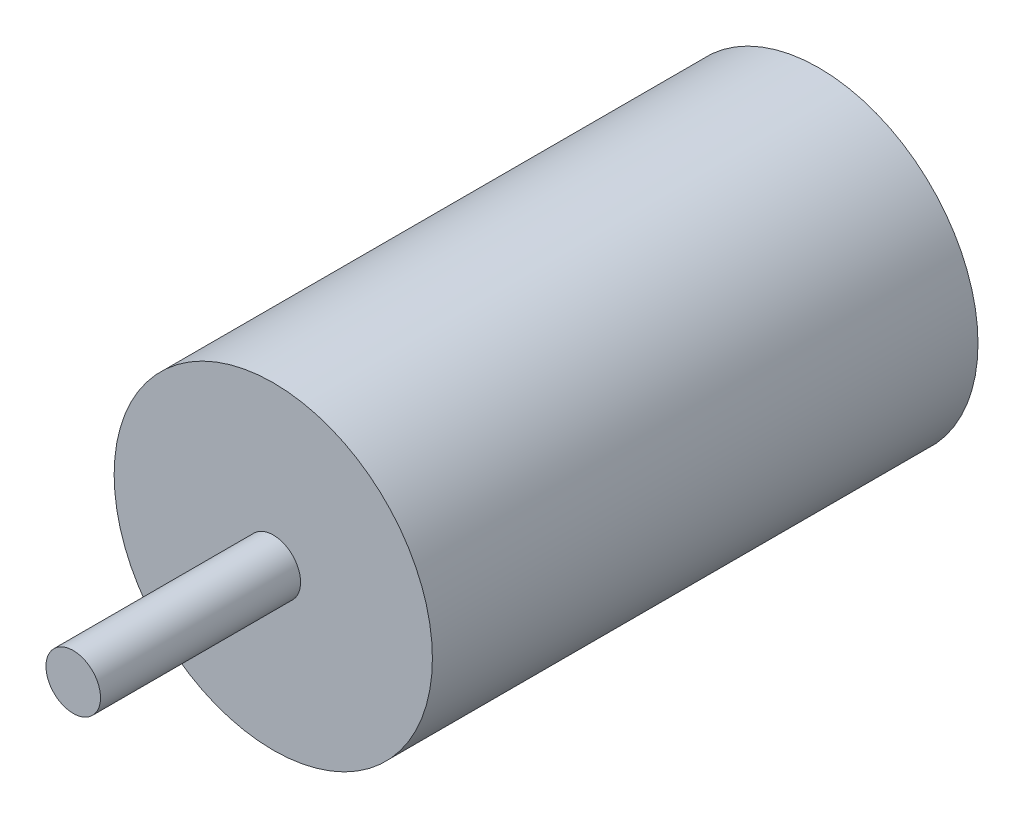
SolidWorks part; units mm, degrees
ref_plane "Front Plane" through (0, 0, 0) normal (0, 0, 1) x (1, 0, 0)
ref_plane "Top Plane" through (0, 0, 0) normal (0, 1, 0) x (1, 0, 0)
ref_plane "Right Plane" through (0, 0, 0) normal (1, 0, 0) x (0, 0, -1)
sketch "Sketch1" plane through (0, 0, 0) normal (0, 0, 1) x (1, 0, 0)
  circle A0 centre (0, 0) radius 17.5
extrude "Boss-Extrude1" add sketch "Sketch1" along normal blind 60
sketch "Sketch2" plane through (0, 0, 60) normal (0, 0, 1) x (1, 0, 0)
  circle A0 centre (0, 0) radius 3
extrude "Boss-Extrude2" add sketch "Sketch2" along normal blind 22
